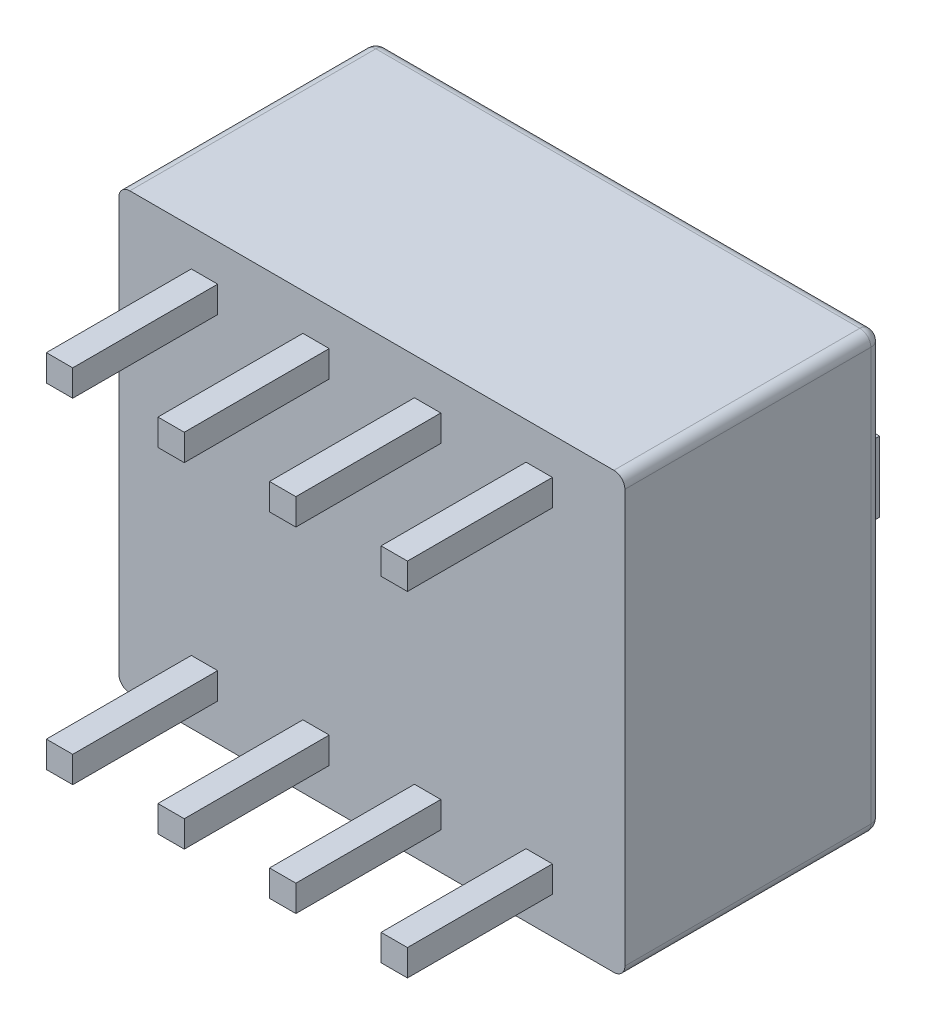
SolidWorks part; units mm, degrees
ref_plane "Ön Düzlem" through (0, 0, 0) normal (0, 0, 1) x (1, 0, 0)
ref_plane "Üst Düzlem" through (0, 0, 0) normal (0, 1, 0) x (1, 0, 0)
ref_plane "Sağ Düzlem" through (0, 0, 0) normal (1, 0, 0) x (0, 0, -1)
sketch "Çizim1" plane through (0, 0, 0) normal (0, 0, 1) x (1, 0, 0)
  line L1 (-5.76, 4.95) -> (5.76, 4.95)
  line L2 (-5.76, 4.95) -> (-5.76, -4.95)
  line L3 (-5.76, -4.95) -> (5.76, -4.95)
  line L4 (5.76, 4.95) -> (5.76, -4.95)
  line L5 (-5.76, 4.95) -> (5.76, -4.95) construction
  line L6 (-5.76, -4.95) -> (5.76, 4.95) construction
  point P0 (0, 0)
extrude "Yükseklik-Ekstrüzyon1" add sketch "Çizim1" along normal blind 5.85
sketch "Çizim2" plane through (0, 0, 0) normal (0, 0, -1) x (-1, 0, 0)
  line L7 (4.51, 1.6) -> (3.11, 1.6)
  line L8 (4.51, 1.6) -> (4.51, -1.6)
  line L9 (4.51, -1.6) -> (3.11, -1.6)
  line L10 (3.11, 1.6) -> (3.11, -1.6)
  line L11 (4.51, 1.6) -> (3.11, -1.6) construction
  line L12 (4.51, -1.6) -> (3.11, 1.6) construction
  line L13 (1.97, 1.6) -> (0.57, 1.6)
  line L14 (1.97, 1.6) -> (1.97, -1.6)
  line L15 (1.97, -1.6) -> (0.57, -1.6)
  line L16 (0.57, 1.6) -> (0.57, -1.6)
  line L17 (1.97, 1.6) -> (0.57, -1.6) construction
  line L18 (1.97, -1.6) -> (0.57, 1.6) construction
  line L19 (-0.57, -1.6) -> (-1.97, -1.6)
  line L20 (-0.57, -1.6) -> (-0.57, 1.6)
  line L21 (-0.57, 1.6) -> (-1.97, 1.6)
  line L22 (-1.97, -1.6) -> (-1.97, 1.6)
  line L23 (-0.57, -1.6) -> (-1.97, 1.6) construction
  line L24 (-0.57, 1.6) -> (-1.97, -1.6) construction
  line L25 (-3.11, 1.6) -> (-4.51, 1.6)
  line L26 (-3.11, 1.6) -> (-3.11, -1.6)
  line L27 (-3.11, -1.6) -> (-4.51, -1.6)
  line L28 (-4.51, 1.6) -> (-4.51, -1.6)
  line L29 (-3.11, 1.6) -> (-4.51, -1.6) construction
  line L30 (-3.11, -1.6) -> (-4.51, 1.6) construction
extrude "Kes-Ekstrüzyon1" cut sketch "Çizim2" against normal blind 1
sketch "Çizim4" plane through (0, 0, 1) normal (0, 0, -1) x (-1, 0, 0)
  line L0 (3.11, 1.6) -> (3.11, -1.6) construction
  line L1 (4.51, 1.6) -> (3.11, 1.6)
  line L2 (4.51, 1.6) -> (4.51, 0)
  line L3 (4.51, 0) -> (3.11, 0)
  line L4 (3.11, 1.6) -> (3.11, 0)
  line L5 (0.57, 1.6) -> (0.57, -1.6) construction
  line L6 (1.97, 1.6) -> (0.57, 1.6)
  line L7 (1.97, 1.6) -> (1.97, 0)
  line L8 (1.97, 0) -> (0.57, 0)
  line L9 (0.57, 1.6) -> (0.57, 0)
  line L10 (-1.97, 1.6) -> (-1.97, -1.6) construction
  line L11 (-0.57, 1.6) -> (-1.97, 1.6)
  line L12 (-0.57, 1.6) -> (-0.57, 0)
  line L13 (-0.57, 0) -> (-1.97, 0)
  line L14 (-1.97, 1.6) -> (-1.97, 0)
  line L15 (-4.51, 1.6) -> (-4.51, -1.6) construction
  line L16 (-3.11, 1.6) -> (-4.51, 1.6)
  line L17 (-3.11, 1.6) -> (-3.11, 0)
  line L18 (-3.11, 0) -> (-4.51, 0)
  line L19 (-4.51, 1.6) -> (-4.51, 0)
extrude "Yükseklik-Ekstrüzyon2" add sketch "Çizim4" along normal blind 2.2 separate body
sketch "Çizim5" plane through (0, 0, 1) normal (0, 0, -1) x (-1, 0, 0)
  line L0 (-1.97, 1.6) -> (-1.97, -1.6) construction
  line L1 (-4.51, 0) -> (-3.11, 0)
  line L2 (-4.51, 0) -> (-4.51, -1.6)
  line L3 (-4.51, -1.6) -> (-3.11, -1.6)
  line L4 (-3.11, 0) -> (-3.11, -1.6)
  line L5 (-1.97, 0) -> (-0.57, 0)
  line L6 (-1.97, 0) -> (-1.97, -1.6)
  line L7 (-1.97, -1.6) -> (-0.57, -1.6)
  line L8 (-0.57, 0) -> (-0.57, -1.6)
  line L9 (0.57, 1.6) -> (0.57, -1.6) construction
  line L10 (0.57, 0) -> (1.97, 0)
  line L11 (0.57, 0) -> (0.57, -1.6)
  line L12 (0.57, -1.6) -> (1.97, -1.6)
  line L13 (1.97, 0) -> (1.97, -1.6)
  line L14 (3.11, 1.6) -> (3.11, -1.6) construction
  line L15 (3.11, 0) -> (4.51, 0)
  line L16 (3.11, 0) -> (3.11, -1.6)
  line L17 (3.11, -1.6) -> (4.51, -1.6)
  line L18 (4.51, 0) -> (4.51, -1.6)
extrude "Yükseklik-Ekstrüzyon3" add sketch "Çizim5" along normal blind 0.9 separate body
fillet "Radyus1" radius 0.25 8 edges at (-5.76, 4.95, 2.925) (5.76, 4.95, 2.925) (0, 4.95, 0) (-5.76, 0, 0) (-5.76, -4.95, 2.925) (0, -4.95, 0) (5.76, -4.95, 2.925) (5.76, 0, 0)
sketch "Çizim6" plane through (0, 0, 5.85) normal (0, 0, 1) x (1, 0, 0)
  line L11 (4.11, 4.11) -> (3.51, 4.11)
  line L12 (4.11, 4.11) -> (4.11, 3.51)
  line L13 (4.11, 3.51) -> (3.51, 3.51)
  line L14 (3.51, 4.11) -> (3.51, 3.51)
  line L15 (4.11, 4.11) -> (3.51, 3.51) construction
  line L16 (4.11, 3.51) -> (3.51, 4.11) construction
  line L17 (1.57, 4.11) -> (0.97, 4.11)
  line L18 (1.57, 4.11) -> (1.57, 3.51)
  line L19 (1.57, 3.51) -> (0.97, 3.51)
  line L20 (0.97, 4.11) -> (0.97, 3.51)
  line L21 (1.57, 4.11) -> (0.97, 3.51) construction
  line L22 (1.57, 3.51) -> (0.97, 4.11) construction
  line L23 (-0.97, 4.11) -> (-1.57, 4.11)
  line L24 (-0.97, 4.11) -> (-0.97, 3.51)
  line L25 (-0.97, 3.51) -> (-1.57, 3.51)
  line L26 (-1.57, 4.11) -> (-1.57, 3.51)
  line L27 (-0.97, 4.11) -> (-1.57, 3.51) construction
  line L28 (-0.97, 3.51) -> (-1.57, 4.11) construction
  line L29 (-3.51, 4.11) -> (-4.11, 4.11)
  line L30 (-3.51, 4.11) -> (-3.51, 3.51)
  line L31 (-3.51, 3.51) -> (-4.11, 3.51)
  line L32 (-4.11, 4.11) -> (-4.11, 3.51)
  line L33 (-3.51, 4.11) -> (-4.11, 3.51) construction
  line L34 (-3.51, 3.51) -> (-4.11, 4.11) construction
  line L35 (4.11, -3.51) -> (3.51, -3.51)
  line L36 (4.11, -3.51) -> (4.11, -4.11)
  line L37 (4.11, -4.11) -> (3.51, -4.11)
  line L38 (3.51, -3.51) -> (3.51, -4.11)
  line L39 (4.11, -3.51) -> (3.51, -4.11) construction
  line L40 (4.11, -4.11) -> (3.51, -3.51) construction
  line L41 (1.57, -3.51) -> (0.97, -3.51)
  line L42 (1.57, -3.51) -> (1.57, -4.11)
  line L43 (1.57, -4.11) -> (0.97, -4.11)
  line L44 (0.97, -3.51) -> (0.97, -4.11)
  line L45 (1.57, -3.51) -> (0.97, -4.11) construction
  line L46 (1.57, -4.11) -> (0.97, -3.51) construction
  line L47 (-0.97, -3.51) -> (-1.57, -3.51)
  line L48 (-0.97, -3.51) -> (-0.97, -4.11)
  line L49 (-0.97, -4.11) -> (-1.57, -4.11)
  line L50 (-1.57, -3.51) -> (-1.57, -4.11)
  line L51 (-0.97, -3.51) -> (-1.57, -4.11) construction
  line L52 (-0.97, -4.11) -> (-1.57, -3.51) construction
  line L53 (-3.51, -3.51) -> (-4.11, -3.51)
  line L54 (-3.51, -3.51) -> (-3.51, -4.11)
  line L55 (-3.51, -4.11) -> (-4.11, -4.11)
  line L56 (-4.11, -3.51) -> (-4.11, -4.11)
  line L57 (-3.51, -3.51) -> (-4.11, -4.11) construction
  line L58 (-3.51, -4.11) -> (-4.11, -3.51) construction
extrude "Yükseklik-Ekstrüzyon4" add sketch "Çizim6" along normal blind 3.3
